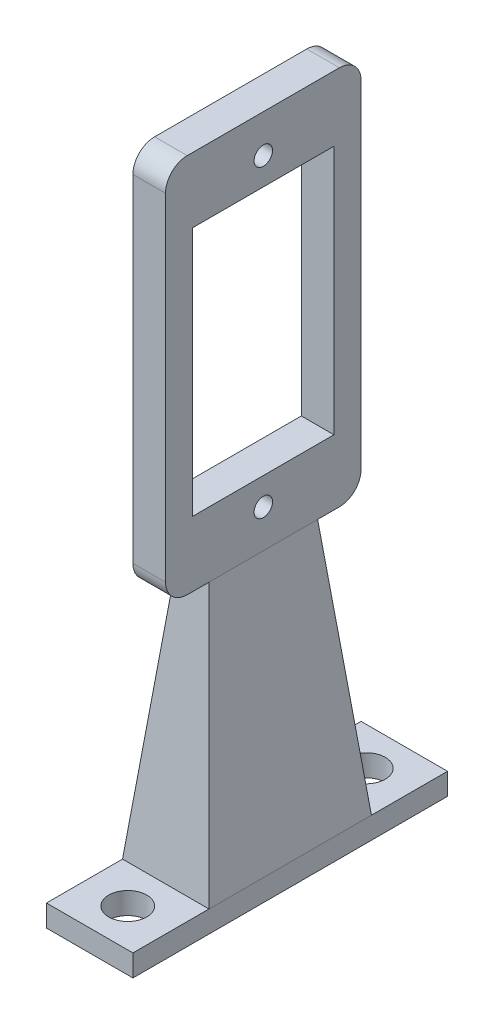
SolidWorks part; units mm, degrees
ref_plane "Plano frontal" through (0, 0, 0) normal (0, 0, 1) x (1, 0, 0)
ref_plane "Plano superior" through (0, 0, 0) normal (0, 1, 0) x (1, 0, 0)
ref_plane "Plano direito" through (0, 0, 0) normal (1, 0, 0) x (0, 0, -1)
sketch "Esboço1" plane through (0, 0, 0) normal (1, 0, 0) x (0, 0, -1)
  line L1 (-9, -17.5) -> (9, -17.5)
  line L2 (-9, -17.5) -> (-9, 17.5)
  line L3 (-9, 17.5) -> (9, 17.5)
  line L4 (9, -17.5) -> (9, 17.5)
  line L5 (-9, -17.5) -> (9, 17.5) construction
  line L6 (-9, 17.5) -> (9, -17.5) construction
  point P0 (0, 0)
  dimension "D1" = 35
  dimension "D2" = 18
extrude "Ressalto-extrusão1" add sketch "Esboço1" along normal mid plane 3
sketch "Esboço2" plane through (1.5, 0, 0) normal (1, 0, 0) x (0, 0, -1)
  line L1 (6.5, -11.5) -> (-6.5, -11.5)
  line L2 (6.5, -11.5) -> (6.5, 11.5)
  line L3 (6.5, 11.5) -> (-6.5, 11.5)
  line L4 (-6.5, -11.5) -> (-6.5, 11.5)
  line L5 (6.5, -11.5) -> (-6.5, 11.5) construction
  line L6 (6.5, 11.5) -> (-6.5, -11.5) construction
  point P0 (0, 0)
  dimension "D1" = 13
  dimension "D2" = 23
extrude "Corte-extrusão1" cut sketch "Esboço2" against normal up to next
sketch "Esboço3" plane through (-1.5, 0, 0) normal (-1, 0, 0) x (0, 0, 1)
  line L0 (-12.3301, 0) -> (12.3301, 0) construction
  circle A0 centre (0, 14) radius 0.85
  circle A1 centre (0, -14) radius 0.85
  dimension "D1" = 1.7
  dimension "D2" = 14
extrude "Corte-extrusão2" cut sketch "Esboço3" against normal up to next
fillet "Filete1" radius 2 4 edges at (0, -17.5, 9) (0, -17.5, -9) (0, 17.5, 9) (0, 17.5, -9)
sketch "Esboço4" plane through (0, -17.5, 0) normal (0, -1, 0) x (1, 0, 0)
  line L1 (-1.5, -5) -> (1.5, -5)
  line L2 (-1.5, -5) -> (-1.5, 5)
  line L3 (-1.5, 5) -> (1.5, 5)
  line L4 (1.5, -5) -> (1.5, 5)
  line L5 (1.5, -7) -> (1.5, 7) construction
  line L6 (-1.5, -7) -> (-1.5, 7) construction
  point P8 (1.5, 0)
  dimension "D1" = 10
extrude "Ressalto-extrusão2" add sketch "Esboço4" along normal blind 23.57 draft 6
sketch "Esboço5" plane through (0, -41.07, 0) normal (0, -1, 0) x (1, 0, 0)
  line L1 (3.9773, -7.4773) -> (3.9773, 7.4773) construction
  line L2 (-3.9773, 14.4773) -> (3.9773, 14.4773)
  line L3 (-3.9773, 14.4773) -> (-3.9773, -14.4773)
  line L4 (-3.9773, -14.4773) -> (3.9773, -14.4773)
  line L5 (3.9773, 14.4773) -> (3.9773, -14.4773)
  line L6 (-3.9773, 7.4773) -> (-3.9773, -7.4773) construction
  line L9 (3.9773, 7.4773) -> (-3.9773, 7.4773) construction
  point P10 (-3.9773, 0)
  dimension "D1" = 7
extrude "Ressalto-extrusão3" add sketch "Esboço5" along normal blind 2
sketch "Esboço6" plane through (0, -41.07, 0) normal (0, 1, 0) x (1, 0, 0)
  line L0 (-3.9773, 0) -> (3.9773, 0) construction
  line L1 (-3.9773, -7.4773) -> (-3.9773, 7.4773) construction
  line L2 (3.9773, 7.4773) -> (3.9773, -7.4773) construction
  line L3 (-3.9773, 14.4773) -> (3.9773, 14.4773) construction
  circle A0 centre (0, 10.9773) radius 1.75
  circle A1 centre (0, -10.9773) radius 1.75
  dimension "D1" = 3.5
  dimension "D2" = 3.5
extrude "Corte-extrusão3" cut sketch "Esboço6" against normal up to next
